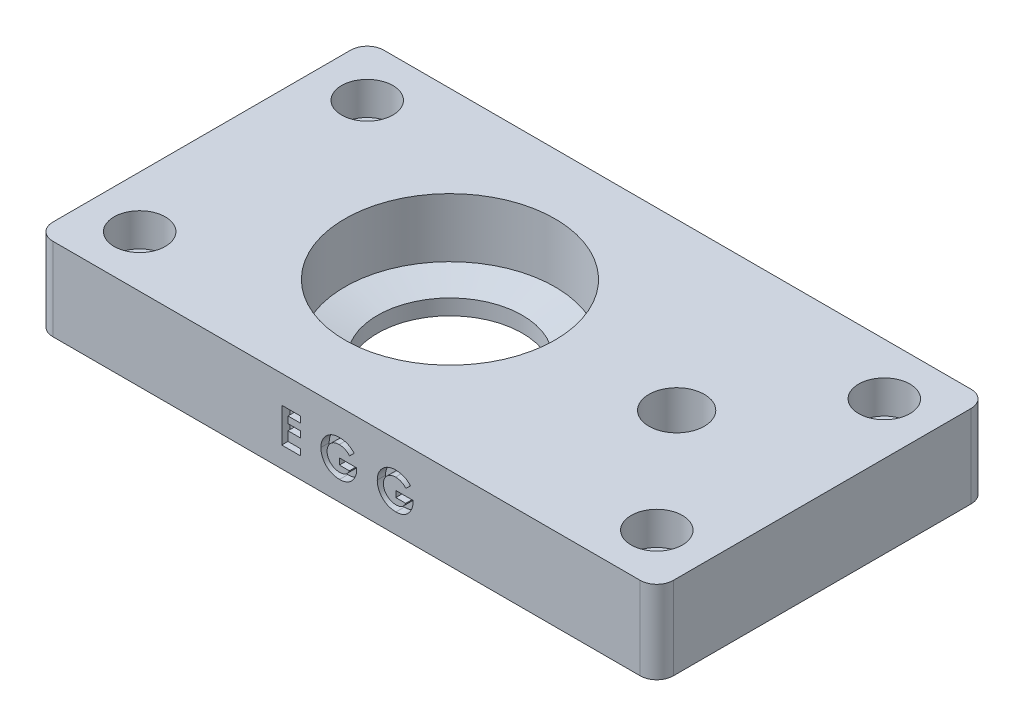
SolidWorks part; units mm, degrees
material "ABS"
ref_plane "Front Plane" through (0, 0, 0) normal (0, 0, 1) x (1, 0, 0)
ref_plane "Top Plane" through (0, 0, 0) normal (0, 1, 0) x (1, 0, 0)
ref_plane "Right Plane" through (0, 0, 0) normal (1, 0, 0) x (0, 0, -1)
sketch "Sketch1" plane through (0, 0, 0) normal (0, 1, 0) x (1, 0, 0)
  line L0 (0, 0) -> (34.798, 0) construction
  line L1 (-38.1, -25.4) -> (57.15, -25.4)
  line L2 (-38.1, -25.4) -> (-38.1, 25.4)
  line L3 (-38.1, 25.4) -> (57.15, 25.4)
  line L4 (57.15, -25.4) -> (57.15, 25.4)
  point P0 (0, 0)
  dimension "D1" = 95.25
  dimension "D2" = 50.8
  dimension "D3" = 34.798
extrude "Boss-Extrude1" add sketch "Sketch1" along normal blind 12.7
sketch "Sketch4" plane through (0, 12.7, 0) normal (0, 1, 0) x (1, 0, 0)
  line L5 (57.15, -25.4) -> (57.15, 25.4) construction
  line L6 (-38.1, -25.4) -> (57.15, -25.4) construction
  line L7 (57.15, 25.4) -> (-38.1, 25.4) construction
  line L8 (-38.1, 25.4) -> (-38.1, -25.4) construction
  circle A0 centre (-30.1625, 17.4625) radius 2.54
  circle A1 centre (49.2125, 17.4625) radius 2.54
  circle A2 centre (49.2125, -17.4625) radius 2.54
  circle A3 centre (-30.1625, -17.4625) radius 2.54
  point P0 (0, 0)
  dimension "D3" = 5.08
  dimension "D4" = 5.08
  dimension "D5" = 5.08
  dimension "D6" = 5.08
  dimension "D1" = 7.9375
  dimension "D2" = 7.9375
  dimension "D9" = 7.9375
  dimension "D7" = 7.9375
  dimension "D8" = 7.9375
  dimension "D10" = 7.9375
  dimension "D11" = 7.9375
  dimension "D12" = 7.9375
extrude "Cut-Extrude3" cut sketch "Sketch4" against normal through all
fillet "Fillet2" radius 2.54 4 edges at (-38.1, 6.35, 25.4) (57.15, 6.35, 25.4) (57.15, 6.35, -25.4) (-38.1, 6.35, -25.4)
sketch "Sketch6" plane through (0, 0, 0) normal (0, 0, 1) x (1, 0, 0)
  line L0 (0, 0) -> (0, 12.7)
  line L1 (-35.56, 12.7) -> (54.61, 12.7) construction
  line L2 (0, 12.7) -> (-16.129, 12.7)
  line L3 (-16.129, 12.7) -> (-16.129, 3.6513)
  line L5 (-35.56, 0) -> (54.61, 0) construction
  line L6 (-11.1125, 0) -> (0, 0)
  line L7 (-11.1125, 0) -> (-11.1125, 2.3813)
  line L8 (-11.1125, 2.3813) -> (-16.129, 3.6513)
  line L9 (-38.1, 0) -> (-38.1, 12.7) construction
  dimension "D1" = 16.129
  dimension "D2" = 11.1125
  dimension "D3" = 1.27
  dimension "D4" = 2.3813
  dimension "D5" = 38.1
revolve "Cut-Revolve1" cut sketch "Sketch6" angle 360 about L0
sketch "Sketch8" plane through (0, 12.7, 0) normal (0, 1, 0) x (1, 0, 0)
  line L0 (57.15, -22.86) -> (57.15, 22.86) construction
  circle A1 centre (34.798, 0) radius 4.25
  circle A2 centre (0, 0) radius 11.1125 construction
  point P5 (57.15, 0)
  dimension "D1" = 34.798
  dimension "D2" = 8.5
extrude "Cut-Extrude4" cut sketch "Sketch8" against normal blind 6.35
sketch "Sketch9" plane through (0, 0, 25.4) normal (0, 0, 1) x (1, 0, 0)
  line L0 (-35.56, 3.175) -> (54.61, 3.175) construction
  line L1 (-35.56, 12.7) -> (-35.56, 0) construction
  line L2 (54.61, 0) -> (54.61, 12.7) construction
  text T0 "<b>EGG</b>" font "Century Gothic" height in points 20
  point P6 (-35.56, 6.35)
  dimension "D1" = 3.175
extrude "Cut-Extrude5" cut sketch "Sketch9" against normal blind 1.27
sketch "Sketch10" plane through (0, 12.7, 0) normal (0, 1, 0) x (1, 0, 0)
  circle A0 centre (-30.1625, 17.4625) radius 3.937
  circle A1 centre (-30.1625, -17.4625) radius 3.937
  circle A2 centre (49.2125, 17.4625) radius 3.937
  circle A3 centre (49.2125, -17.4625) radius 3.937
  dimension "D1" = 7.874
  dimension "D2" = 7.874
  dimension "D3" = 7.874
  dimension "D4" = 7.874
extrude "Cut-Extrude6" cut sketch "Sketch10" against normal blind 5.08
